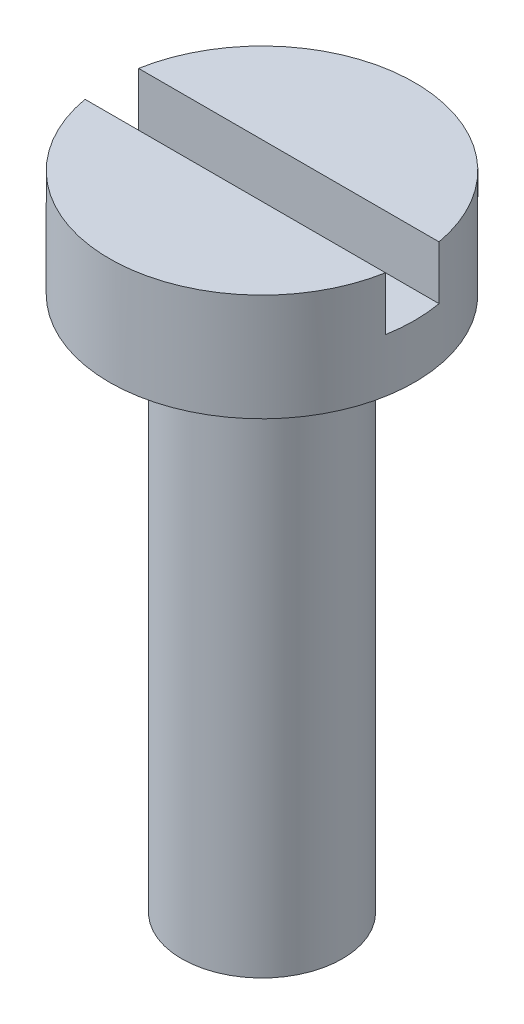
SolidWorks part; units mm, degrees
ref_plane "Front Plane" through (0, 0, 0) normal (0, 0, 1) x (1, 0, 0)
ref_plane "Top Plane" through (0, 0, 0) normal (0, 1, 0) x (1, 0, 0)
ref_plane "Right Plane" through (0, 0, 0) normal (1, 0, 0) x (0, 0, -1)
sketch "Sketch1" plane through (0, 0, 0) normal (0, 1, 0) x (1, 0, 0)
  circle A0 centre (0, 0) radius 2.85
  dimension "D1" = 5.7
extrude "Boss-Extrude1" add sketch "Sketch1" along normal blind 2
sketch "Sketch2" plane through (0, 0, 0) normal (0, 1, 0) x (1, 0, 0)
  circle A0 centre (0, 0) radius 1.5
  dimension "D1" = 3
extrude "Boss-Extrude2" add sketch "Sketch2" against normal blind 10
sketch "Sketch3" plane through (0, 2, 0) normal (0, 1, 0) x (1, 0, 0)
  line L1 (-3, -0.5) -> (3, -0.5)
  line L2 (-3, -0.5) -> (-3, 0.5)
  line L3 (-3, 0.5) -> (3, 0.5)
  line L4 (3, -0.5) -> (3, 0.5)
  line L5 (-3, -0.5) -> (3, 0.5) construction
  line L6 (-3, 0.5) -> (3, -0.5) construction
  point P0 (0, 0)
  dimension "D1" = 1
  dimension "D2" = 6
extrude "Cut-Extrude1" cut sketch "Sketch3" against normal blind 1
